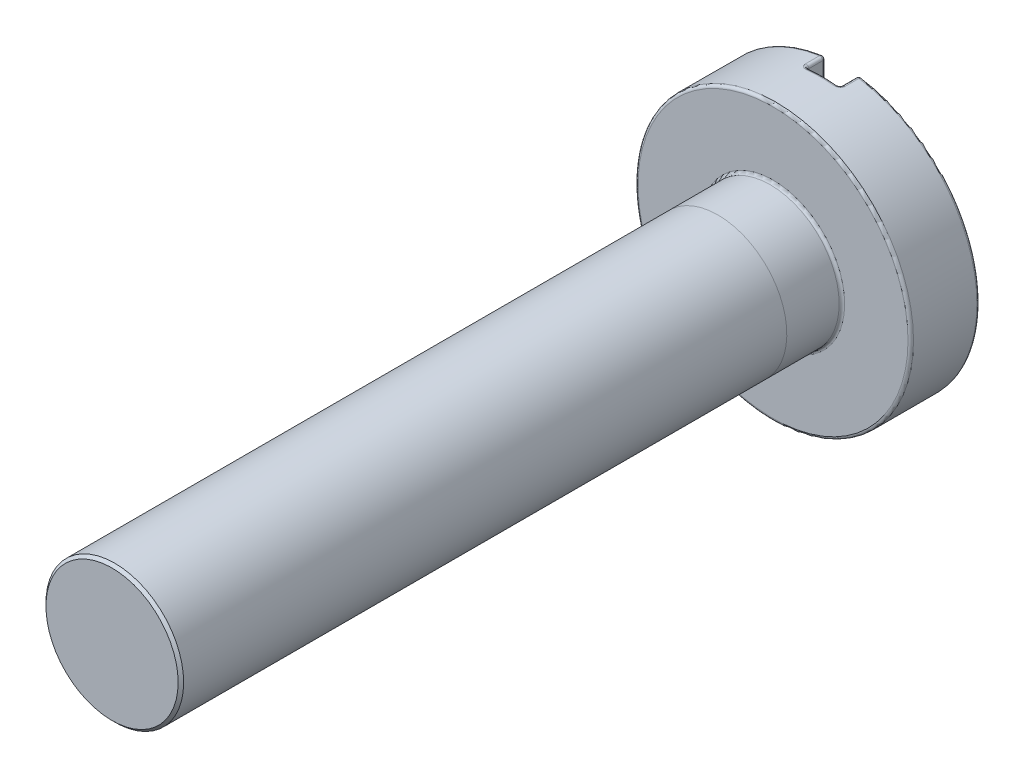
SolidWorks part; units mm, degrees
ref_plane "Front Plane" through (0, 0, 0) normal (0, 0, 1) x (1, 0, 0)
ref_plane "Top Plane" through (0, 0, 0) normal (0, 1, 0) x (1, 0, 0)
ref_plane "Right Plane" through (0, 0, 0) normal (1, 0, 0) x (0, 0, -1)
sketch "Sketch1" plane through (0, 0, 0) normal (0, 0, 1) x (1, 0, 0)
  circle A0 centre (0, 0) radius 1.25
  dimension "D1" = 2.5
extrude "Boss-Extrude1" add sketch "Sketch1" along normal blind 12
sketch "Sketch2" plane through (0, 0, 0) normal (0, 0, 1) x (1, 0, 0)
  circle A2 centre (0, 0) radius 2.5
  circle A3 centre (0, 0) radius 2.5
  dimension "D1" = 1.25
extrude "Boss-Extrude2" add sketch "Sketch2" against normal blind 1.25
sketch "Sketch3" plane through (0, 0, -1.25) normal (0, 0, -1) x (-1, 0, 0)
  line L1 (-0.3, 4.1969) -> (0.3, 4.1969)
  line L2 (-0.3, 4.1969) -> (-0.3, -4.1969)
  line L3 (-0.3, -4.1969) -> (0.3, -4.1969)
  line L4 (0.3, 4.1969) -> (0.3, -4.1969)
  line L5 (-0.3, 4.1969) -> (0.3, -4.1969) construction
  line L6 (-0.3, -4.1969) -> (0.3, 4.1969) construction
  point P0 (0, 0)
  dimension "D1" = 0.6
extrude "Cut-Extrude1" cut sketch "Sketch3" against normal blind 0.35
fillet "Fillet1" radius 0.05 13 edges at (0.3, 2.4819, -1.075) (0.3, -2.4819, -1.075) (-0.3, -2.4819, -1.075) (-0.3, 2.4819, -1.075) (0, -2.5, -0.9) (0, 2.5, -0.9) (0.3, 0, -0.9) (-0.3, 0, -0.9) (0.3, 0, -1.25) (2.5, 0, -1.25) (-0.3, 0, -1.25) (-2.5, 0, -1.25) (1.25, 0, 0)
fillet "Fillet2" radius 0.05 1 edges at (2.5, 0, 0)
chamfer "Chamfer1" distance 0.05 angle 45 1 edges at (1.25, 0, 12)
sketch "Sketch4" plane through (0, 0, 0) normal (1, 0, 0) x (0, 0, -1)
  line L0 (-1, 3.701) -> (-1, -3.2348)
  line L1 (-12, 1.2) -> (-12, -1.2) construction
  dimension "D1" = 11
split line "Split Line1"
